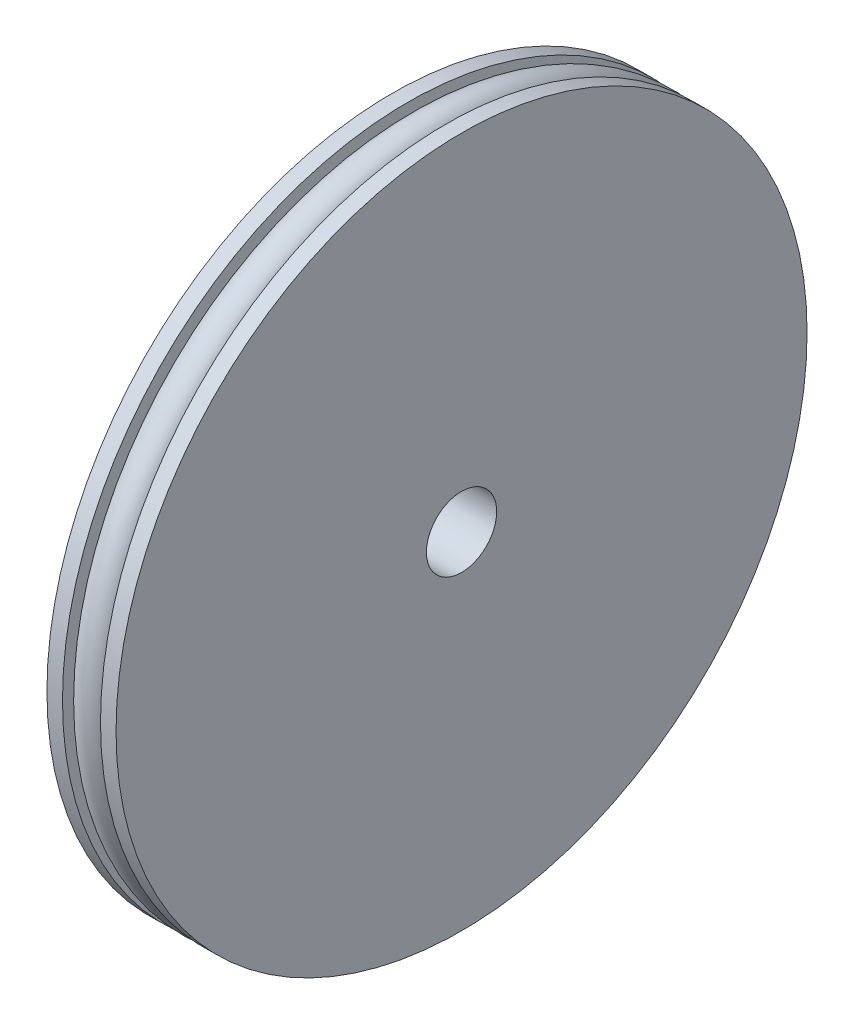
SolidWorks part; units mm, degrees
ref_plane "Plan de face" through (0, 0, 0) normal (0, 0, 1) x (1, 0, 0)
ref_plane "Plan de dessus" through (0, 0, 0) normal (0, 1, 0) x (1, 0, 0)
ref_plane "Plan de droite" through (0, 0, 0) normal (1, 0, 0) x (0, 0, -1)
sketch "Esquisse1" plane through (0, 0, 0) normal (0, 0, 1) x (1, 0, 0)
  line L0 (1.35, 30) -> (1.35, 25)
  line L1 (0, 0) -> (6, 0)
  line L2 (0, 0) -> (0, 30)
  line L3 (0, 30) -> (1.35, 30)
  line L4 (6, 0) -> (6, 30)
  line L5 (1.35, 25) -> (4.65, 25)
  line L6 (4.65, 25) -> (4.65, 30)
  line L7 (4.65, 30) -> (6, 30)
  dimension "D1" = 30
  dimension "D2" = 6
  dimension "D3" = 3.3
  dimension "D5" = 5
revolve "Révolution1" add sketch "Esquisse1" angle 360 about L1
sketch "Esquisse2" plane through (0, 0, 0) normal (0, 0, 1) x (1, 0, 0)
  line L0 (4.65, 25) -> (1.35, 25)
  line L1 (1.35, 25) -> (1.35, 28.35)
  line L2 (4.65, 25) -> (4.65, 28.35)
  line L3 (-10.3309, 0) -> (62.6388, 0)
  line L4 (4.65, 25) -> (1.35, 25) construction
  line L5 (4.65, 30) -> (4.65, -30) construction
  line L6 (1.35, -30) -> (1.35, 30) construction
  line L7 (1.35, 30) -> (0, 30) construction
  arc A0 (4.65, 28.35) -> (1.35, 28.35) centre (3, 28.35) ccw
  point P14 (62.6388, 0)
  point P15 (0, 0)
  dimension "D1" = 0
  dimension "D2" = 0
  dimension "D3" = 0
revolve "Révolution2" add sketch "Esquisse2" angle 360 about L3
sketch "Esquisse3" plane through (0, 0, 0) normal (-1, 0, 0) x (0, 0, 1)
  circle A0 centre (0, 0) radius 7.5228
extrude "Boss.-Extru.1" add sketch "Esquisse3" along normal blind 8
sketch "Esquisse4" plane through (-8, 0, 0) normal (-1, 0, 0) x (0, 0, 1)
  circle A0 centre (0, 0) radius 3.05
  dimension "D1" = 6.1
extrude "Enlèv. mat.-Extru.1" cut sketch "Esquisse4" against normal through all
